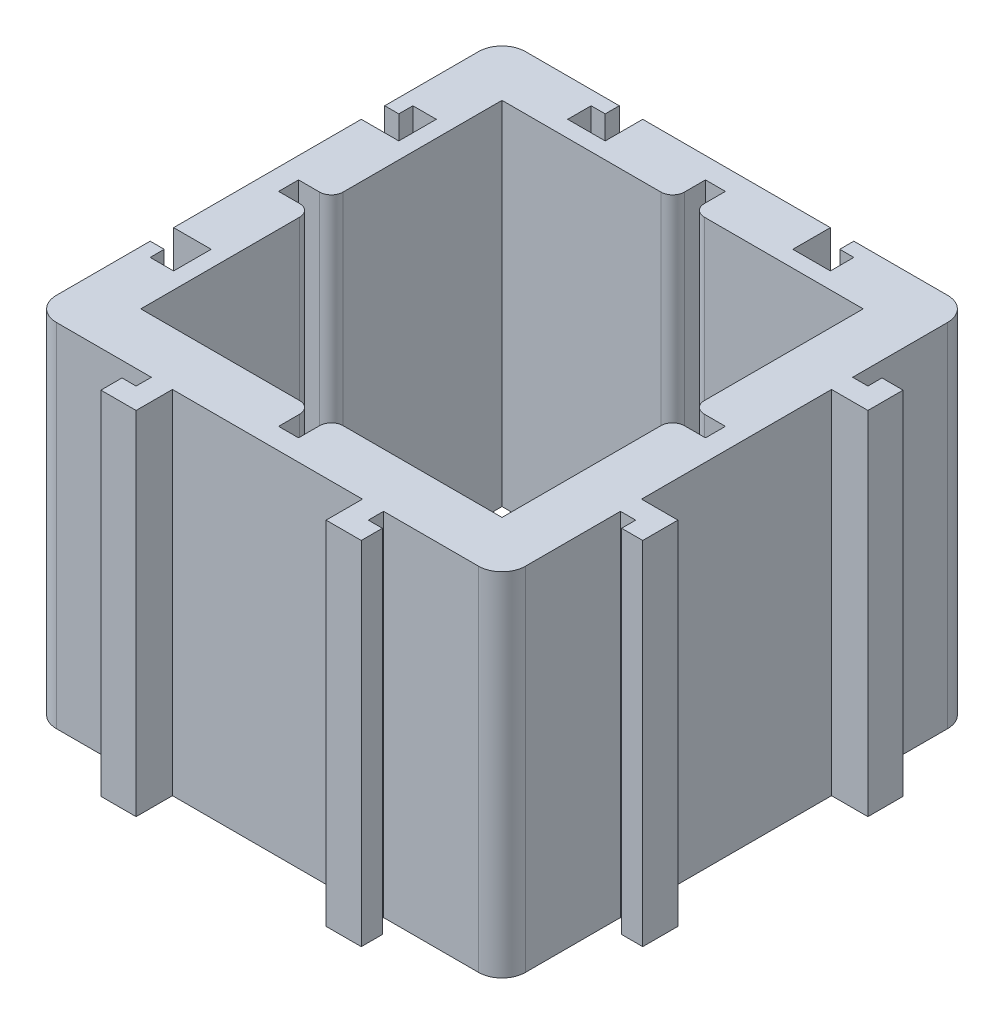
SolidWorks part; units mm, degrees
ref_plane "Front Plane" through (0, 0, 0) normal (0, 0, 1) x (1, 0, 0)
ref_plane "Top Plane" through (0, 0, 0) normal (0, 1, 0) x (1, 0, 0)
ref_plane "Right Plane" through (0, 0, 0) normal (1, 0, 0) x (0, 0, -1)
sketch "Sketch1" plane through (0, 0, 0) normal (0, 1, 0) x (1, 0, 0)
  line L0 (-25.4, 0) -> (25.4, 0) construction
  line L1 (19.558, -19.558) -> (1.0795, -19.558)
  line L2 (19.558, -19.558) -> (19.558, -1.0795)
  line L3 (19.558, 19.558) -> (1.0795, 19.558)
  line L4 (-19.558, -19.558) -> (-19.558, -1.0795)
  line L5 (19.558, -19.558) -> (-19.558, 19.558) construction
  line L6 (19.558, 19.558) -> (-19.558, -19.558) construction
  line L7 (25.4, -25.4) -> (-25.4, -25.4)
  line L8 (25.4, -25.4) -> (25.4, 25.4)
  line L9 (25.4, 25.4) -> (-25.4, 25.4)
  line L10 (-25.4, -25.4) -> (-25.4, 25.4)
  line L11 (25.4, -25.4) -> (-25.4, 25.4) construction
  line L12 (25.4, 25.4) -> (-25.4, -25.4) construction
  line L13 (0, 25.4) -> (0, -25.4) construction
  line L14 (-19.558, 1.0795) -> (-19.558, 19.558)
  line L15 (-19.558, 1.0795) -> (-23.114, 1.0795)
  line L17 (-19.558, -1.0795) -> (-23.114, -1.0795)
  line L18 (-23.114, 1.0795) -> (-23.114, -1.0795)
  line L19 (-19.558, 1.0795) -> (-23.114, 1.0795)
  line L20 (-19.558, -1.0795) -> (-23.114, -1.0795)
  line L21 (19.558, -1.0795) -> (23.114, -1.0795)
  line L22 (23.114, 1.0795) -> (23.114, -1.0795)
  line L23 (19.558, 1.0795) -> (23.114, 1.0795)
  line L24 (1.0795, -19.558) -> (1.0795, -23.114)
  line L25 (-1.0795, -23.114) -> (1.0795, -23.114)
  line L26 (-1.0795, -19.558) -> (-1.0795, -23.114)
  line L27 (1.0795, 19.558) -> (1.0795, 23.114)
  line L28 (-1.0795, 23.114) -> (1.0795, 23.114)
  line L29 (-1.0795, 19.558) -> (-1.0795, 23.114)
  line L30 (-1.0795, 19.558) -> (-19.558, 19.558)
  line L31 (19.558, 1.0795) -> (19.558, 19.558)
  line L32 (-1.0795, -19.558) -> (-19.558, -19.558)
  point P0 (0, 0)
  point P6 (0, 0)
  dimension "D2" = 39.116
  dimension "D3" = 50.8
  dimension "D4" = 50.8
  dimension "D5" = 3.556
  dimension "D6" = 2.159
extrude "Boss-Extrude1" add sketch "Sketch1" along normal blind 38.1 contours L10 L7 L8 L9 L26 L32 L4 L17 L18 L15 L14 L30 L29 L28 L27 L3 L31 L23 L22 L21 L2 L1 L24 L25
fillet "Fillet1" radius 2.54 4 edges at (25.4, 19.05, 25.4) (25.4, 19.05, -25.4) (-25.4, 19.05, -25.4) (-25.4, 19.05, 25.4)
fillet "Fillet2" radius 1.27 8 edges at (-19.558, 19.05, -1.0795) (-19.558, 19.05, 1.0795) (-1.0795, 19.05, -19.558) (1.0795, 19.05, -19.558) (-1.0795, 19.05, 19.558) (1.0795, 19.05, 19.558) (19.558, 19.05, 1.0795) (19.558, 19.05, -1.0795)
sketch "Sketch3" plane through (0, 38.1, 0) normal (0, 1, 0) x (1, 0, 0)
  line L0 (-25.4, -22.86) -> (-25.4, 22.86) construction
  line L1 (-25.4, 10.16) -> (-21.336, 10.16)
  line L2 (-25.4, 10.16) -> (-25.4, 12.7)
  line L3 (-25.4, 12.7) -> (-23.876, 12.7)
  line L4 (-21.336, 10.16) -> (-21.336, 12.7)
  line L5 (22.86, 25.4) -> (-22.86, 25.4) construction
  line L6 (-21.336, 10.16) -> (-23.876, 10.16)
  line L7 (-21.336, 10.16) -> (-21.336, 14.224)
  line L8 (-21.336, 14.224) -> (-23.876, 14.224)
  line L9 (-23.876, 12.7) -> (-23.876, 14.224)
  line L10 (-25.4, 0) -> (25.4, 0) construction
  line L11 (25.4, -22.86) -> (25.4, 22.86) construction
  line L20 (0, 25.4) -> (0, -25.4) construction
  line L21 (22.86, -25.4) -> (-22.86, -25.4) construction
  line L22 (-25.4, 10.16) -> (-21.336, 10.16)
  line L23 (-25.4, 10.16) -> (-25.4, 12.7)
  line L24 (-25.4, 12.7) -> (-23.876, 12.7)
  line L25 (-21.336, 10.16) -> (-21.336, 12.7)
  line L26 (-21.336, 10.16) -> (-23.876, 10.16)
  line L27 (-21.336, 10.16) -> (-21.336, 14.224)
  line L28 (-21.336, 14.224) -> (-23.876, 14.224)
  line L29 (-23.876, 12.7) -> (-23.876, 14.224)
  line L30 (-21.336, -10.16) -> (-21.336, -12.7)
  line L31 (-23.876, -12.7) -> (-21.336, -12.7)
  line L33 (-23.876, -10.16) -> (-21.336, -10.16)
  line L37 (-23.876, -10.16) -> (-23.876, -12.7)
  line L38 (-23.876, -12.7) -> (-23.876, -14.224)
  line L39 (-21.336, -14.224) -> (-23.876, -14.224)
  line L48 (-23.876, 10.16) -> (-23.876, 12.7)
  line L49 (-23.876, 10.16) -> (-21.336, 10.16)
  line L50 (-23.876, 12.7) -> (-21.336, 12.7)
  line L55 (-21.336, 10.16) -> (-21.336, 12.7)
  line L64 (-21.336, -10.16) -> (-21.336, -14.224)
  line L65 (-21.336, -10.16) -> (-23.876, -10.16)
  line L66 (-21.336, -10.16) -> (-21.336, -12.7)
  line L69 (-25.4, -12.7) -> (-23.876, -12.7)
  line L70 (-25.4, -10.16) -> (-25.4, -12.7)
  line L80 (-24.6561, 24.6561) -> (24.6561, -24.6561) construction
  line L82 (-25.4, -10.16) -> (-21.336, -10.16)
  line L83 (-23.876, -12.7) -> (-23.876, -14.224)
  line L86 (-21.336, -14.224) -> (-23.876, -14.224)
  line L87 (-21.336, -10.16) -> (-21.336, -14.224)
  line L88 (-21.336, -10.16) -> (-23.876, -10.16)
  line L97 (-21.336, -10.16) -> (-21.336, -12.7)
  line L98 (-25.4, -12.7) -> (-23.876, -12.7)
  line L99 (-25.4, -10.16) -> (-25.4, -12.7)
  line L102 (-25.4, -10.16) -> (-21.336, -10.16)
  line L103 (10.16, 25.4) -> (10.16, 21.336)
  line L104 (10.16, 25.4) -> (12.7, 25.4)
  line L113 (12.7, 25.4) -> (12.7, 23.876)
  line L114 (10.16, 21.336) -> (12.7, 21.336)
  line L115 (10.16, 21.336) -> (10.16, 23.876)
  line L118 (10.16, 21.336) -> (14.224, 21.336)
  line L119 (14.224, 21.336) -> (14.224, 23.876)
  line L120 (12.7, 23.876) -> (14.224, 23.876)
  line L129 (10.16, 25.4) -> (10.16, 21.336)
  line L130 (10.16, 25.4) -> (12.7, 25.4)
  line L131 (12.7, 25.4) -> (12.7, 23.876)
  line L134 (10.16, 21.336) -> (12.7, 21.336)
  line L135 (10.16, 21.336) -> (10.16, 23.876)
  line L136 (10.16, 21.336) -> (14.224, 21.336)
  line L145 (-10.16, 21.336) -> (-12.7, 21.336)
  line L146 (-12.7, 23.876) -> (-12.7, 21.336)
  line L147 (-10.16, 23.876) -> (-10.16, 21.336)
  line L148 (-10.16, 23.876) -> (-12.7, 23.876)
  line L149 (14.224, 21.336) -> (14.224, 23.876)
  line L150 (12.7, 23.876) -> (14.224, 23.876)
  line L151 (10.16, 23.876) -> (12.7, 23.876)
  line L152 (10.16, 23.876) -> (10.16, 21.336)
  line L153 (12.7, 23.876) -> (12.7, 21.336)
  line L154 (10.16, 21.336) -> (12.7, 21.336)
  line L155 (-12.7, 23.876) -> (-14.224, 23.876)
  line L156 (-14.224, 21.336) -> (-14.224, 23.876)
  line L157 (-10.16, 21.336) -> (-14.224, 21.336)
  line L158 (-10.16, 21.336) -> (-10.16, 23.876)
  line L159 (-10.16, 21.336) -> (-12.7, 21.336)
  line L160 (-12.7, 25.4) -> (-12.7, 23.876)
  line L161 (-10.16, 25.4) -> (-12.7, 25.4)
  line L162 (-10.16, 25.4) -> (-10.16, 21.336)
  line L163 (-12.7, 23.876) -> (-14.224, 23.876)
  line L164 (-14.224, 21.336) -> (-14.224, 23.876)
  line L165 (-10.16, 21.336) -> (-14.224, 21.336)
  line L166 (-10.16, 21.336) -> (-10.16, 23.876)
  line L167 (-10.16, 21.336) -> (-12.7, 21.336)
  line L168 (-12.7, 25.4) -> (-12.7, 23.876)
  line L169 (-10.16, 25.4) -> (-12.7, 25.4)
  line L170 (-10.16, 25.4) -> (-10.16, 21.336)
  arc A0 (-22.86, 25.4) -> (-25.4, 22.86) centre (-22.86, 22.86) ccw construction
  arc A1 (22.86, -25.4) -> (25.4, -22.86) centre (22.86, -22.86) ccw construction
  line M14 (22.86, 25.4) -> (-22.86, 25.4)
  line M16 (-25.4, 22.86) -> (-25.4, -22.86)
  dimension "D2" = 2.54
  dimension "D5" = 12.7
  dimension "D4" = 4.064
  dimension "D1" = 2.54
  dimension "D3" = 4.064
extrude "Cut-Extrude1" cut sketch "Sketch3" against normal through all contours L1 L48 L3 M16 | L50 L48 L1 L4 | L9 L50 L7 L8 | L82 L69 L37 M16 | L33 L37 L31 L30 | L64 L31 L38 L39 | L162 L160 L148 M14 | L147 L148 L146 L145 | L157 L146 L155 L156 | L103 L151 L113 M14 | L153 L151 L103 L114 | L120 L153 L118 L119
sketch "Sketch5" plane through (0, 38.1, 0) normal (0, 1, 0) x (1, 0, 0)
  line L0 (-25.4, -10.16) -> (25.4, -10.16) construction
  line L1 (25.4, -22.86) -> (25.4, 22.86) construction
  line L2 (-25.4, -12.7) -> (25.4, -12.7) construction
  line L3 (-23.876, -14.224) -> (12.7, -14.224) construction
  line L4 (-25.4, 0) -> (25.4, 0) construction
  line L13 (-25.4, -10.16) -> (-25.4, 10.16) construction
  line L22 (25.4, -22.86) -> (25.4, 22.86) construction
  line L31 (27.051, -10.287) -> (27.051, -14.097)
  line L32 (29.337, -14.097) -> (27.051, -14.097)
  line L33 (29.337, -10.287) -> (29.337, -14.097)
  line L34 (29.337, -10.287) -> (27.051, -10.287)
  line L35 (29.337, -10.287) -> (29.337, -12.573)
  line L36 (25.4, -12.573) -> (29.337, -12.573)
  line L37 (25.4, -10.287) -> (25.4, -12.573)
  line L38 (25.4, -10.287) -> (29.337, -10.287)
  line L40 (25.4, 10.287) -> (29.337, 10.287)
  line L41 (25.4, 10.287) -> (25.4, 12.573)
  line L42 (25.4, 12.573) -> (29.337, 12.573)
  line L43 (29.337, 10.287) -> (29.337, 12.573)
  line L44 (29.337, 10.287) -> (27.051, 10.287)
  line L45 (29.337, 10.287) -> (29.337, 14.097)
  line L46 (29.337, 14.097) -> (27.051, 14.097)
  line L47 (27.051, 10.287) -> (27.051, 14.097)
  line L48 (-24.6561, 24.6561) -> (24.6561, -24.6561) construction
  line L49 (-10.287, -27.051) -> (-14.097, -27.051)
  line L50 (-14.097, -29.337) -> (-14.097, -27.051)
  line L51 (-10.287, -29.337) -> (-14.097, -29.337)
  line L52 (-10.287, -29.337) -> (-10.287, -27.051)
  line L53 (-10.287, -29.337) -> (-12.573, -29.337)
  line L54 (-12.573, -25.4) -> (-12.573, -29.337)
  line L55 (-10.287, -25.4) -> (-10.287, -29.337)
  line L56 (10.287, -25.4) -> (10.287, -29.337)
  line L57 (12.573, -25.4) -> (12.573, -29.337)
  line L58 (10.287, -29.337) -> (12.573, -29.337)
  line L59 (10.287, -29.337) -> (10.287, -27.051)
  line L60 (10.287, -29.337) -> (14.097, -29.337)
  line L61 (14.097, -29.337) -> (14.097, -27.051)
  line L62 (10.287, -27.051) -> (14.097, -27.051)
  line L63 (22.86, -25.4) -> (-22.86, -25.4) construction
  line L64 (12.573, -25.4) -> (10.287, -25.4)
  line L65 (-10.287, -25.4) -> (-12.573, -25.4)
  arc A0 (-22.86, 25.4) -> (-25.4, 22.86) centre (-22.86, 22.86) ccw construction
  arc A1 (22.86, -25.4) -> (25.4, -22.86) centre (22.86, -22.86) ccw construction
  dimension "D1" = 2.286
  dimension "D2" = 3.937
  dimension "D3" = 3.81
  dimension "D4" = 2.286
  dimension "D5" = 11.303
extrude "Boss-Extrude2" add sketch "Sketch5" against normal up to surface (38.1 mm away) contours L49 L54 L51 L52 | L55 L65 L54 L49 | L54 L49 L50 L51 | L62 L56 L58 L57 | L62 L57 L60 L61 | L57 L64 L56 L62 | L31 L36 L33 L34 | L36 L31 L32 L33 | L38 L37 L36 L31 | L47 L42 L45 L46 | L47 L40 L43 L42 | L40 L47 L42 L41 up to face at (0, 0, 0)
equation "\"L\"= 2in"
equation "\"D3@Sketch1\"=\"L\""
equation "\"D4@Sketch1\"=\"L\""
equation "\"D2@Sketch1\"=0.75*\"L\"+0.04"
equation "\"D5@Sketch1\"=0.1*0.75*\"L\"-0.01"
equation "\"D6@Sketch1\"=0.05*0.75*\"L\"+0.01"
equation "\"D2@Sketch3\"=0.05*\"L\""
equation "\"D5@Sketch3\"=0.25*\"L\""
equation "\"D4@Sketch3\"=0.08*\"L\""
equation "\"D1@Sketch3\"=0.05*\"L\""
equation "\"D3@Sketch3\"=0.08*\"L\""
equation "\"D1@Sketch5\"=0.05*\"L\"-0.01"
equation "\"D2@Sketch5\"=0.08*\"L\"-0.005"
equation "\"D3@Sketch5\"=0.08*\"L\"-0.01"
equation "\"D4@Sketch5\"=0.05*\"L\"-0.01"
equation "\"D5@Sketch5\"=0.22*\"L\"+0.005"
equation "\"1.5n\"=4"
